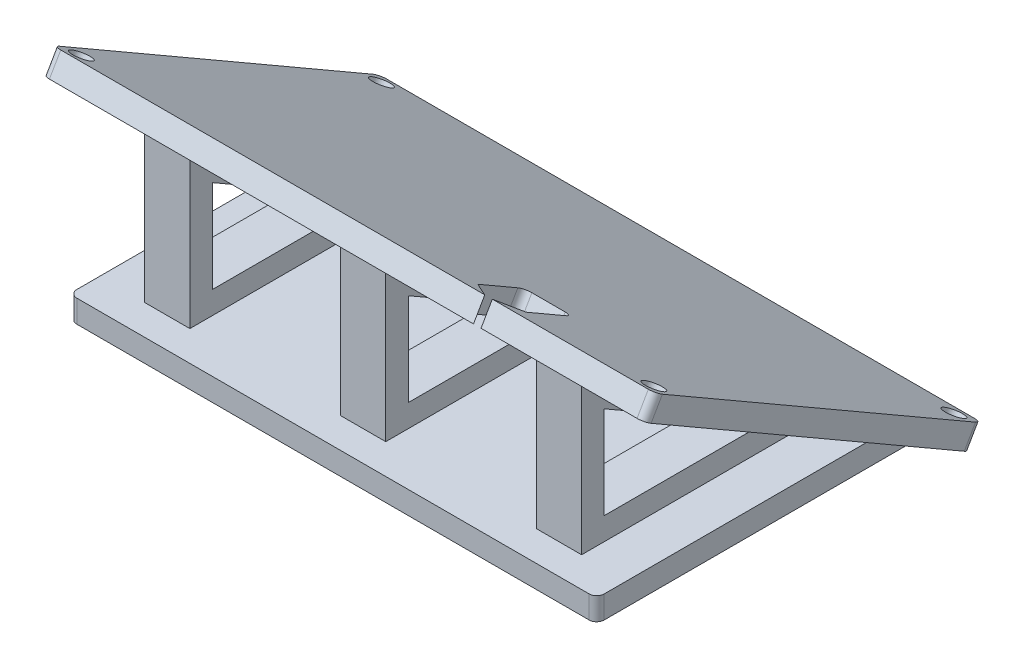
SolidWorks part; units mm, degrees
ref_plane "Front Plane" through (0, 0, 0) normal (0, 0, 1) x (1, 0, 0)
ref_plane "Top Plane" through (0, 0, 0) normal (0, 1, 0) x (1, 0, 0)
ref_plane "Right Plane" through (0, 0, 0) normal (1, 0, 0) x (0, 0, -1)
sketch "Sketch8" plane through (0, 0, 0) normal (0, 1, 0) x (1, 0, 0)
  line L1 (0, 0) -> (70, 0)
  line L2 (0, 0) -> (0, 36)
  line L3 (0, 36) -> (70, 36)
  line L4 (70, 0) -> (70, 36)
extrude "Boss-Extrude3" add sketch "Sketch8" along normal blind 3
sketch "Sketch9" plane through (0, 3, 0) normal (0, 1, 0) x (1, 0, 0)
  line L0 (64, 4) -> (58, 4)
  line L1 (70, 36) -> (0, 36) construction
  line L3 (6, 36) -> (12, 36)
  line L4 (6, 36) -> (6, 4)
  line L5 (6, 4) -> (12, 4)
  line L6 (12, 36) -> (12, 4)
  line L8 (58, 36) -> (58, 4)
  line L9 (64, 36) -> (58, 36)
  line L10 (64, 36) -> (64, 4)
  line L11 (38, 36) -> (38, 4)
  line L12 (38, 36) -> (32, 36)
  line L14 (38, 4) -> (32, 4)
  line L15 (32, 36) -> (32, 4)
extrude "Boss-Extrude4" add sketch "Sketch9" along normal blind 20.4752
sketch "Sketch10" plane through (6, 0, 0) normal (-1, 0, 0) x (0, 0, 1)
  line L6 (-36, 23.4752) -> (-36, 3) construction
  line L7 (-36, 5) -> (-4, 23.4752)
  line L8 (-4, 23.4752) -> (-36, 23.4752)
  line L11 (-36, 23.4752) -> (-36, 5)
extrude "Cut-Extrude1" cut sketch "Sketch10" against normal blind 100 contours L7 L8 L11
sketch "Sketch11" plane through (0, 19.3385, -11.1651) normal (0, 0.866, -0.5) x (1, 0, 0)
  line L0 (6, 38.6769) -> (-5, 38.6769)
  line L1 (64, 38.6769) -> (75, 38.6769)
  line L2 (-5, 38.6769) -> (-5, -11.3231)
  line L3 (-5, -11.3231) -> (75, -11.3231)
  line L4 (75, -11.3231) -> (75, 38.6769)
  line L5 (6, 38.6769) -> (64, 38.6769)
extrude "Boss-Extrude5" add sketch "Sketch11" along normal blind 3
sketch "Sketch14" plane through (0, 0, 0) normal (-1, 0, 0) x (0, 0, 1)
  line L8 (-36, 0) -> (-44.6603, 0)
  line L9 (-44.6603, 0) -> (-36, 5)
  line L10 (-36, 5) -> (-36, 0)
extrude "Boss-Extrude6" add sketch "Sketch14" against normal blind 70
sketch "Sketch15" plane through (0, 21.9365, -12.6651) normal (0, 0.866, -0.5) x (1, 0, 0)
  circle A0 centre (-3, 36.6769) radius 1.3
  circle A1 centre (73, 36.6769) radius 1.3
  circle A2 centre (73, -9.3231) radius 1.3
  circle A3 centre (-3, -9.3231) radius 1.3
extrude "Cut-Extrude2" cut sketch "Sketch15" against normal blind 3
sketch "Sketch16" plane through (6, 0, 0) normal (-1, 0, 0) x (0, 0, 1)
  line L4 (-7, 6) -> (-7, 18.2791)
  line L5 (-7, 18.2791) -> (-28.2679, 6)
  line L7 (-28.2679, 6) -> (-7, 6)
extrude "Cut-Extrude3" cut sketch "Sketch16" against normal blind 100
sketch "Sketch17" plane through (0, 0, 0) normal (0, -1, 0) x (1, 0, 0)
  line L0 (70, -44.6603) -> (0, -44.6603) construction
  line L4 (4, -12) -> (66, -12)
  line L5 (66, -2) -> (4, -2)
  line L8 (4, -2) -> (4, -12)
  line L9 (66, -2) -> (66, -12)
  line L13 (4, -42.6603) -> (4, -32.6603)
  line L14 (66, -42.6603) -> (4, -42.6603)
  line L15 (66, -42.6603) -> (66, -32.6603)
  line L16 (4, -32.6603) -> (66, -32.6603)
  point P12 (35, -12)
  dimension "D1" = 2
extrude "Cut-Extrude4" cut sketch "Sketch17" against normal blind 1
fillet "Fillet1" radius 1 6 edges at (75, 1.299, -45.4103) (-5, 1.299, -45.4103) (-5, 26.299, -2.109) (75, 26.299, -2.109) (70, 1.5, 0) (0, 1.5, 0)
sketch "Sketch18" plane through (0, 19.3385, -11.1651) normal (0, -0.866, 0.5) x (1, 0, 0)
  line L0 (58, 8.2735) -> (58, -1.9641) construction
  line L1 (49.5774, 6.2735) -> (49.5774, 9.2735)
  line L3 (56, 6.2735) -> (56, 3.1298)
  line L4 (55, 2.1298) -> (50.5774, 2.1298)
  line L5 (49.5774, 6.2735) -> (49.5774, 3.1298)
  line L7 (-4, 11.3231) -> (74, 11.3231) construction
  line L8 (53.2887, 11.3231) -> (52.2887, 11.3231)
  line L9 (49.5774, 9.2735) -> (52.2887, 11.3231)
  line L10 (56, 6.2735) -> (56, 9.2735)
  line L11 (56, 9.2735) -> (53.2887, 11.3231)
  arc A0 (56, 3.1298) -> (55, 2.1298) centre (55, 3.1298) cw
  arc A1 (50.5774, 2.1298) -> (49.5774, 3.1298) centre (50.5774, 3.1298) cw
  dimension "D1" = 1
  dimension "D2" = 2
extrude "Cut-Extrude5" cut sketch "Sketch18" against normal blind 10
